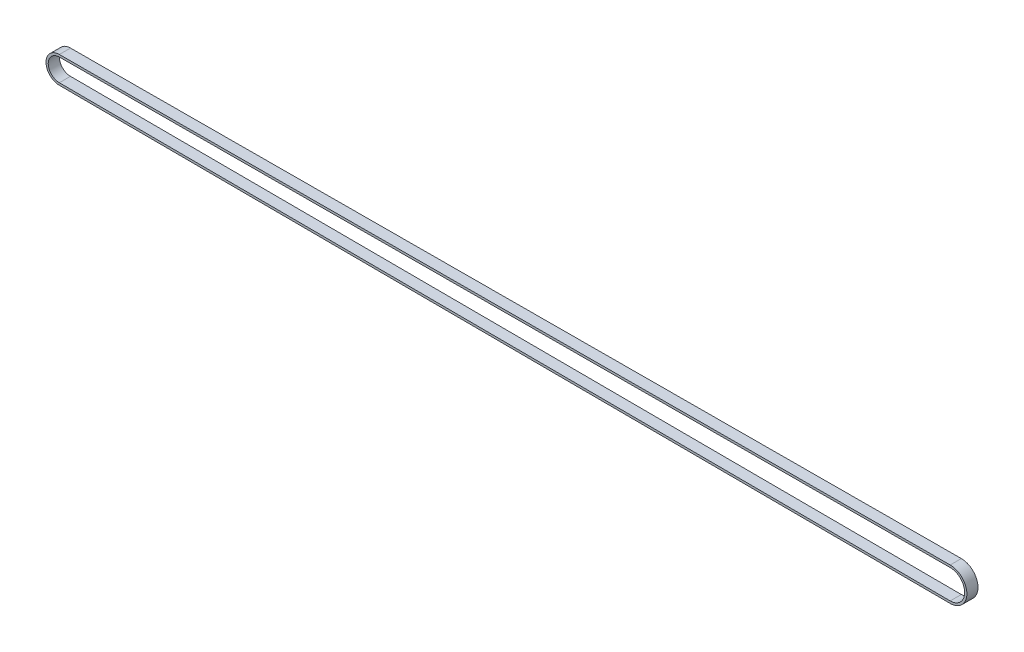
SolidWorks part; units mm, degrees
ref_plane "Plan de face" through (0, 0, 0) normal (0, 0, 1) x (1, 0, 0)
ref_plane "Plan de dessus" through (0, 0, 0) normal (0, 1, 0) x (1, 0, 0)
ref_plane "Plan de droite" through (0, 0, 0) normal (1, 0, 0) x (0, 0, -1)
sketch "Esquisse1" plane through (0, 0, 0) normal (0, 0, 1) x (1, 0, 0)
  line L0 (0, 23.1919) -> (0, -33.2211) construction
  line L1 (0, 0) -> (-400.5, 0) construction
  line L2 (-400.5, 6) -> (-400.5, -7.685) construction
  line L3 (-400.5, 6) -> (0, 7.5)
  line L4 (-400.5, 5) -> (0, 6.5)
  line L5 (-400.5, -5) -> (0, -6.5)
  line L6 (-400.5, -6) -> (0, -7.5)
  arc A0 (0, -6.5) -> (0, 6.5) centre (0, 0) ccw
  arc A1 (0, -7.5) -> (0, 7.5) centre (0, 0) ccw
  arc A2 (-400.5, 6) -> (-400.5, -6) centre (-400.5, 0) ccw
  arc A3 (-400.5, 5) -> (-400.5, -5) centre (-400.5, 0) ccw
  dimension "D1" = 6.5
  dimension "D2" = 7.5
  dimension "D3" = 12
  dimension "D4" = 10
  dimension "D5" = 400.5
extrude "Boss.-Extru.1" add sketch "Esquisse1" along normal blind 5
